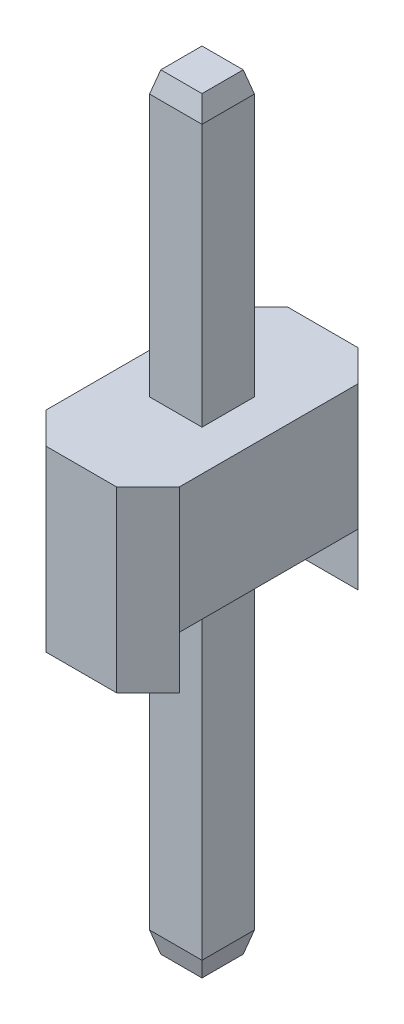
SolidWorks part; units mm, degrees
ref_plane "Front Plane" through (0, 0, 0) normal (0, 0, 1) x (1, 0, 0)
ref_plane "Top Plane" through (0, 0, 0) normal (0, 1, 0) x (1, 0, 0)
ref_plane "Right Plane" through (0, 0, 0) normal (1, 0, 0) x (0, 0, -1)
sketch "Sketch1" plane through (0, 0, 0) normal (0, 1, 0) x (1, 0, 0)
  line L1 (0.635, 1.15) -> (-0.635, 1.15)
  line L2 (0.635, 1.15) -> (0.635, -1.15)
  line L3 (0.635, -1.15) -> (-0.635, -1.15)
  line L4 (-0.635, 1.15) -> (-0.635, -1.15)
  line L5 (0.635, 1.15) -> (-0.635, -1.15) construction
  line L6 (0.635, -1.15) -> (-0.635, 1.15) construction
  point P0 (0, 0)
  dimension "D1" = 2.3
  dimension "D2" = 1.27
extrude "Boss-Extrude1" add sketch "Sketch1" along normal blind 1.7
chamfer "Chamfer1" distance 0.3 angle 45 4 edges at (-0.635, 0.85, -1.15) (0.635, 0.85, -1.15) (0.635, 0.85, 1.15) (-0.635, 0.85, 1.15)
sketch "Sketch2" plane through (0, 0, 0) normal (0, -1, 0) x (1, 0, 0)
  line L2 (-0.635, 0.85) -> (0.635, 0.85)
  line L3 (-0.635, 0.85) -> (-0.635, -0.85)
  line L4 (-0.635, -0.85) -> (0.635, -0.85)
  line L6 (0.635, 0.85) -> (0.635, -0.85)
extrude "Cut-Extrude1" cut sketch "Sketch2" against normal blind 0.5
sketch "Sketch3" plane through (0, 1.7, 0) normal (0, 1, 0) x (1, 0, 0)
  line L1 (-0.25, 0.25) -> (0.25, 0.25)
  line L2 (-0.25, 0.25) -> (-0.25, -0.25)
  line L3 (-0.25, -0.25) -> (0.25, -0.25)
  line L4 (0.25, 0.25) -> (0.25, -0.25)
  line L5 (-0.25, 0.25) -> (0.25, -0.25) construction
  line L6 (-0.25, -0.25) -> (0.25, 0.25) construction
  point P0 (0, 0)
  dimension "D1" = 0.5
extrude "Boss-Extrude2" add sketch "Sketch3" along normal blind 2.7
sketch "Sketch4" plane through (0, 0.5, 0) normal (0, -1, 0) x (1, 0, 0)
  line L0 (-0.25, 0.25) -> (0.25, 0.25) construction
  line L1 (0.25, 0.25) -> (-0.25, 0.25)
  line L2 (0.25, 0.25) -> (0.25, -0.25)
  line L3 (0.25, -0.25) -> (-0.25, -0.25)
  line L4 (-0.25, 0.25) -> (-0.25, -0.25)
  line L5 (0.25, 0.25) -> (-0.25, -0.25) construction
  line L6 (0.25, -0.25) -> (-0.25, 0.25) construction
  point P0 (0, 0)
extrude "Boss-Extrude3" add sketch "Sketch4" along normal offset from surface (3.4 mm away) 7.3 up to face at (0, 4.4, 0)
chamfer "Chamfer3" distance 0.2 angle 15 8 edges at (-0.25, -2.9, 0) (0, -2.9, 0.25) (0.25, -2.9, 0) (0, -2.9, -0.25) (0, 4.4, 0.25) (-0.25, 4.4, 0) (0, 4.4, -0.25) (0.25, 4.4, 0)
